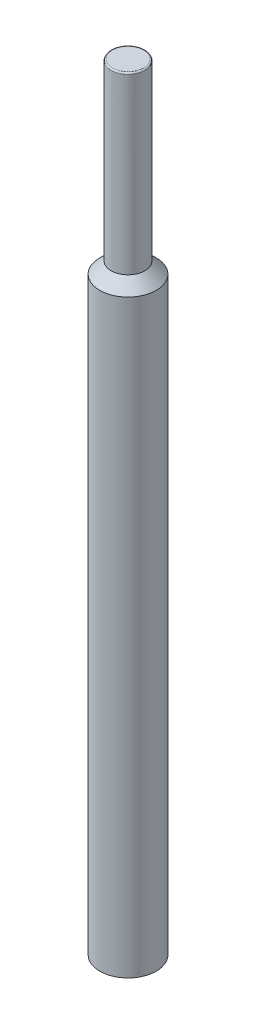
SolidWorks part; units mm, degrees
material "AISI 1020"
ref_plane "Front Plane" through (0, 0, 0) normal (0, 0, 1) x (1, 0, 0)
ref_plane "Top Plane" through (0, 0, 0) normal (0, 1, 0) x (1, 0, 0)
ref_plane "Right Plane" through (0, 0, 0) normal (1, 0, 0) x (0, 0, -1)
sketch "Sketch2" plane through (0, 0, 0) normal (0, 0, 1) x (1, 0, 0)
  line L0 (0, 0) -> (0, 275) construction
  line L1 (0, 0) -> (10, 0)
  line L2 (10, 0) -> (10, 209)
  line L3 (10, 209) -> (6, 213)
  line L4 (6, 213) -> (6, 275)
  line L5 (6, 275) -> (0, 275)
  line L6 (0, 0) -> (0, 275)
  dimension "D1" = 275
  dimension "D2" = 10
  dimension "D3" = 6
  dimension "D4" = 62
  dimension "D5" = 4
revolve "Revolve1" add sketch "Sketch2" angle 360 about L0
fillet "Fillet1" radius 0.5 1 edges at (0, 275, -6)
